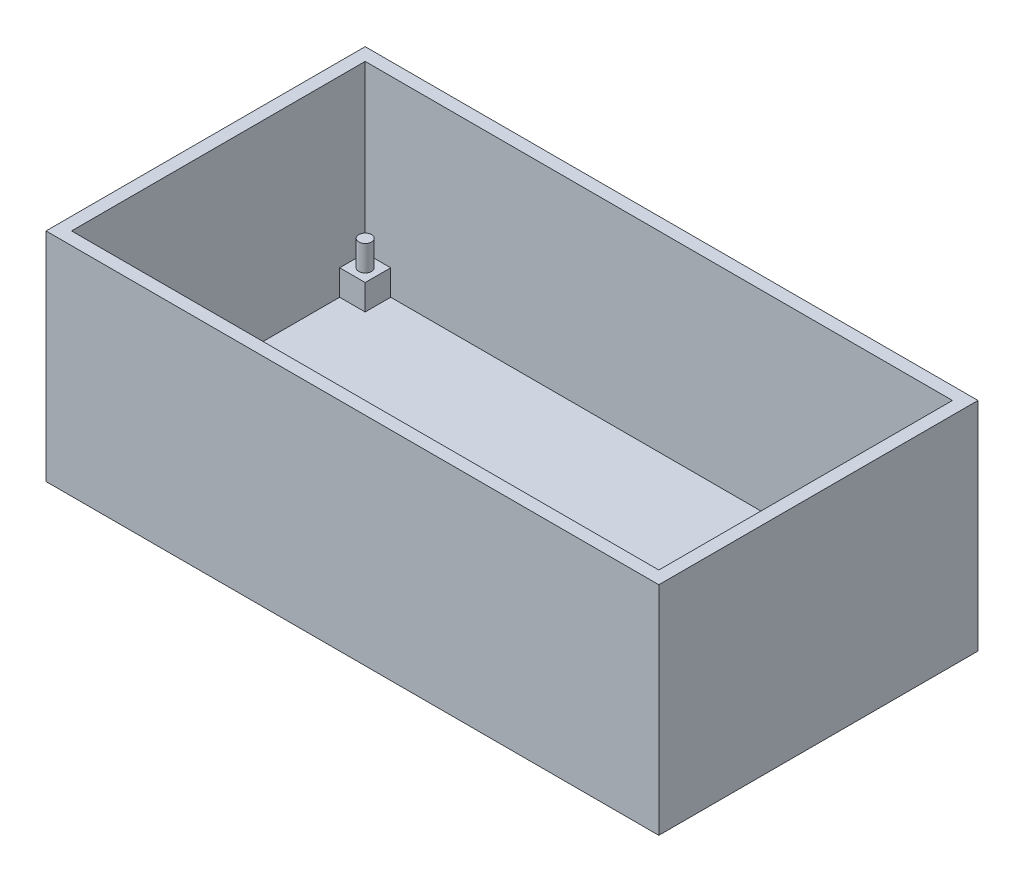
SolidWorks part; units mm, degrees
ref_plane "Front Plane" through (0, 0, 0) normal (0, 0, 1) x (1, 0, 0)
ref_plane "Top Plane" through (0, 0, 0) normal (0, 1, 0) x (1, 0, 0)
ref_plane "Right Plane" through (0, 0, 0) normal (1, 0, 0) x (0, 0, -1)
sketch "Sketch1" plane through (0, 0, 0) normal (0, 1, 0) x (1, 0, 0)
  line L1 (0, 0) -> (121.92, 0)
  line L2 (0, 0) -> (0, 63.5)
  line L3 (0, 63.5) -> (121.92, 63.5)
  line L4 (121.92, 0) -> (121.92, 63.5)
  dimension "D1" = 63.5
  dimension "D2" = 121.92
extrude "Boss-Extrude1" add sketch "Sketch1" along normal blind 5.08
sketch "Sketch2" plane through (0, 5.08, 0) normal (0, 1, 0) x (1, 0, 0)
  line L1 (0, 63.5) -> (121.92, 63.5)
  line L2 (0, 63.5) -> (0, 0)
  line L3 (0, 0) -> (121.92, 0)
  line L4 (121.92, 63.5) -> (121.92, 0)
  line L5 (2.54, 60.96) -> (119.38, 60.96)
  line L6 (2.54, 60.96) -> (2.54, 2.54)
  line L7 (2.54, 2.54) -> (119.38, 2.54)
  line L8 (119.38, 60.96) -> (119.38, 2.54)
  dimension "D1" = 2.54
  dimension "D2" = 2.54
  dimension "D3" = 2.54
  dimension "D4" = 2.54
extrude "Boss-Extrude2" add sketch "Sketch2" along normal blind 38.1
sketch "Sketch4" plane through (0, 5.08, 0) normal (0, 1, 0) x (1, 0, 0)
  line L0 (60.96, 60.96) -> (60.96, 2.54) construction
  line L1 (2.54, 60.96) -> (7.62, 60.96)
  line L2 (2.54, 60.96) -> (2.54, 55.88)
  line L3 (2.54, 55.88) -> (7.62, 55.88)
  line L4 (7.62, 60.96) -> (7.62, 55.88)
  line L5 (119.38, 60.96) -> (2.54, 60.96) construction
  line L6 (2.54, 2.54) -> (119.38, 2.54) construction
  line L7 (2.54, 31.75) -> (119.38, 31.75) construction
  line L8 (2.54, 60.96) -> (2.54, 2.54) construction
  line L9 (119.38, 2.54) -> (119.38, 60.96) construction
  line L10 (114.3, 60.96) -> (114.3, 55.88)
  line L11 (119.38, 55.88) -> (114.3, 55.88)
  line L12 (119.38, 60.96) -> (119.38, 55.88)
  line L13 (119.38, 60.96) -> (114.3, 60.96)
  line L14 (119.38, 2.54) -> (114.3, 2.54)
  line L15 (119.38, 2.54) -> (119.38, 7.62)
  line L16 (119.38, 7.62) -> (114.3, 7.62)
  line L17 (114.3, 2.54) -> (114.3, 7.62)
  line L18 (7.62, 2.54) -> (7.62, 7.62)
  line L19 (2.54, 7.62) -> (7.62, 7.62)
  line L20 (2.54, 2.54) -> (2.54, 7.62)
  line L21 (2.54, 2.54) -> (7.62, 2.54)
  dimension "D1" = 5.08
  dimension "D2" = 5.08
extrude "Boss-Extrude3" add sketch "Sketch4" along normal blind 5.08
sketch "Sketch5" plane through (0, 10.16, 0) normal (0, 1, 0) x (1, 0, 0)
  circle A0 centre (5.08, 58.42) radius 1.27
  circle A1 centre (116.84, 58.42) radius 1.27
  circle A2 centre (116.84, 5.08) radius 1.27
  circle A3 centre (5.08, 5.08) radius 1.27
  dimension "D1" = 2.54
  dimension "D3" = 2.54
  dimension "D4" = 2.54
  dimension "D6" = 2.54
  dimension "D7" = 2.54
  dimension "D9" = 2.54
  dimension "D10" = 2.54
  dimension "D12" = 2.54
  dimension "D2" = 2.54
  dimension "D5" = 2.54
  dimension "D8" = 2.54
  dimension "D11" = 2.54
extrude "Boss-Extrude4" add sketch "Sketch5" along normal blind 5.08
sketch "Sketch6" plane through (0, 0, 0) normal (0, 0, 1) x (1, 0, 0)
  line L1 (10.4441, 18.951) -> (19.9044, 18.951)
  line L2 (10.4441, 18.951) -> (10.4441, 15.5862)
  line L3 (10.4441, 15.5862) -> (19.9044, 15.5862)
  line L4 (19.9044, 18.951) -> (19.9044, 15.5862)
